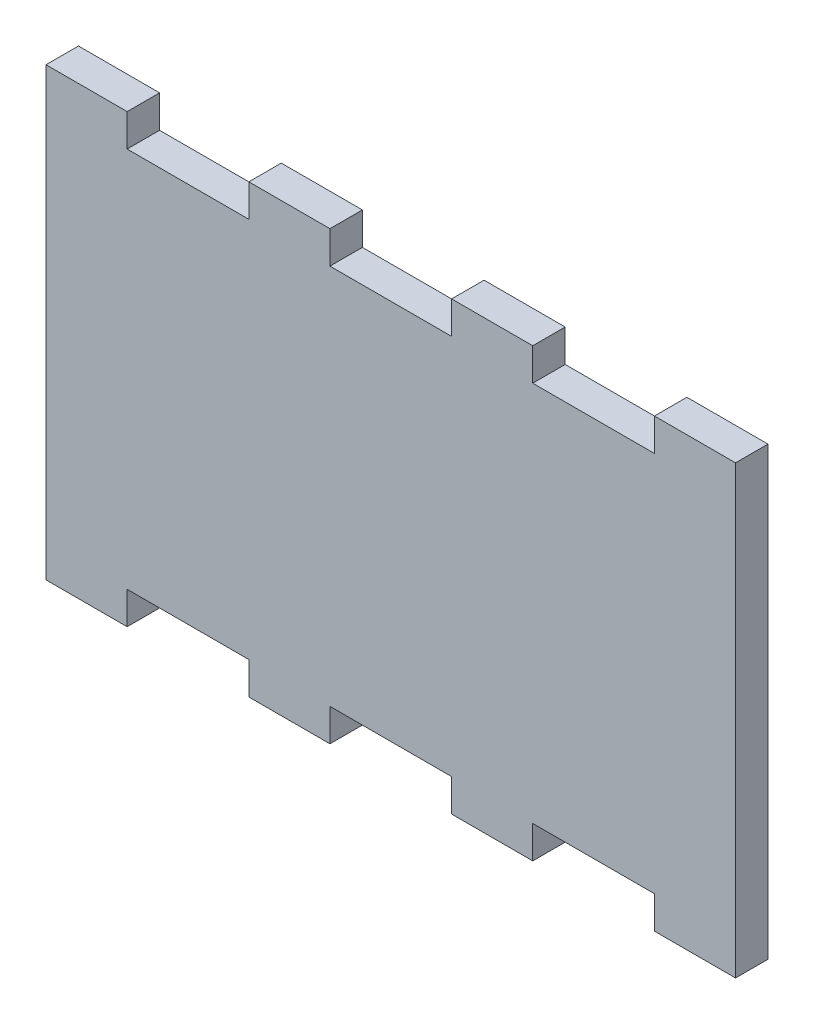
SolidWorks part; units mm, degrees
ref_plane "Alzado" through (0, 0, 0) normal (0, 0, 1) x (1, 0, 0)
ref_plane "Planta" through (0, 0, 0) normal (0, 1, 0) x (1, 0, 0)
ref_plane "Vista lateral" through (0, 0, 0) normal (1, 0, 0) x (0, 0, -1)
sketch "Croquis1" plane through (0, 0, 0) normal (0, 0, 1) x (1, 0, 0)
  line L0 (0, 0) -> (10, 0)
  line L1 (10, 0) -> (10, 4)
  line L2 (10, 4) -> (25, 4)
  line L3 (25, 4) -> (25, 0)
  line L4 (25, 0) -> (35, 0)
  line L5 (35, 0) -> (35, 4)
  line L6 (35, 4) -> (50, 4)
  line L7 (50, 4) -> (50, 0)
  line L8 (50, 0) -> (60, 0)
  line L9 (60, 0) -> (60, 4)
  line L10 (60, 4) -> (75, 4)
  line L11 (75, 4) -> (75, 0)
  line L12 (75, 0) -> (85, 0)
  line L13 (85, 0) -> (85, 55)
  line L14 (0, 0) -> (0, 55)
  line L15 (85, 27.5) -> (0, 27.5) construction
  line L16 (75, 55) -> (85, 55)
  line L17 (75, 51) -> (75, 55)
  line L18 (60, 51) -> (75, 51)
  line L19 (60, 55) -> (60, 51)
  line L20 (50, 55) -> (60, 55)
  line L21 (50, 51) -> (50, 55)
  line L22 (35, 51) -> (50, 51)
  line L23 (35, 55) -> (35, 51)
  line L24 (25, 55) -> (35, 55)
  line L25 (25, 51) -> (25, 55)
  line L26 (10, 51) -> (25, 51)
  line L27 (10, 55) -> (10, 51)
  line L28 (0, 55) -> (10, 55)
  dimension "D1" = 55
  dimension "D2" = 4
  dimension "D3" = 10
  dimension "D4" = 15
extrude "Saliente-Extruir1" add sketch "Croquis1" along normal blind 4
